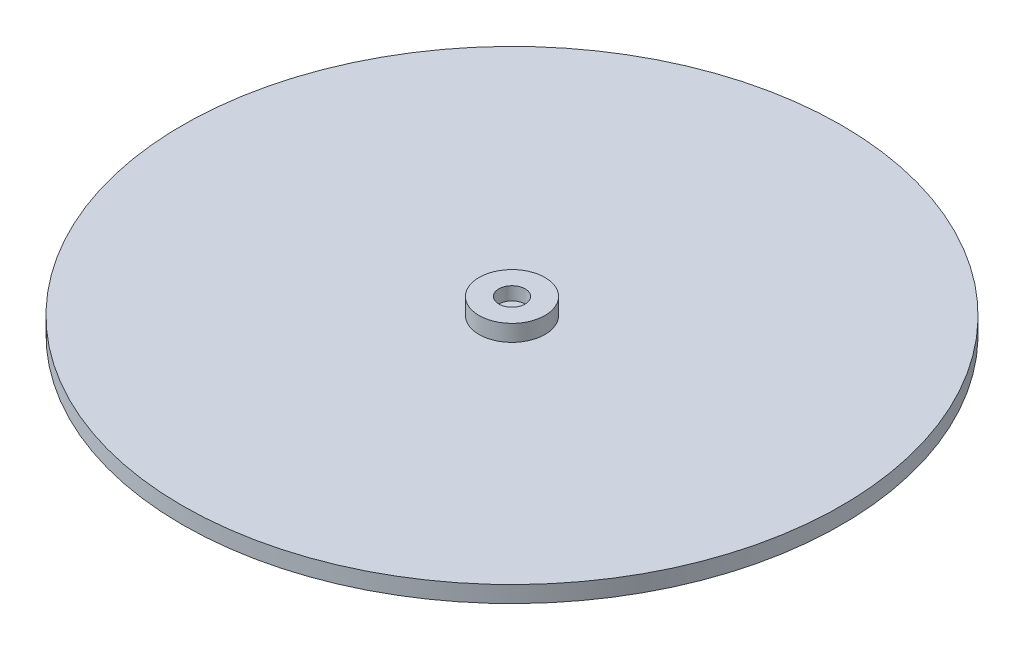
SolidWorks part; units mm, degrees
ref_plane "Front Plane" through (0, 0, 0) normal (0, 0, 1) x (1, 0, 0)
ref_plane "Top Plane" through (0, 0, 0) normal (0, 1, 0) x (1, 0, 0)
ref_plane "Right Plane" through (0, 0, 0) normal (1, 0, 0) x (0, 0, -1)
sketch "Sketch1" plane through (0, 0, 0) normal (0, 1, 0) x (1, 0, 0)
  circle A0 centre (0, 0) radius 500
extrude "Boss-Extrude1" add sketch "Sketch1" along normal blind 25
sketch "Sketch2" plane through (0, 25, 0) normal (0, 1, 0) x (1, 0, 0)
  circle A0 centre (0, 0) radius 50
extrude "Boss-Extrude2" add sketch "Sketch2" along normal blind 25
sketch "Sketch3" plane through (0, 50, 0) normal (0, 1, 0) x (1, 0, 0)
  circle A0 centre (0, 0) radius 20
extrude "Cut-Extrude1" cut sketch "Sketch3" against normal blind 20
